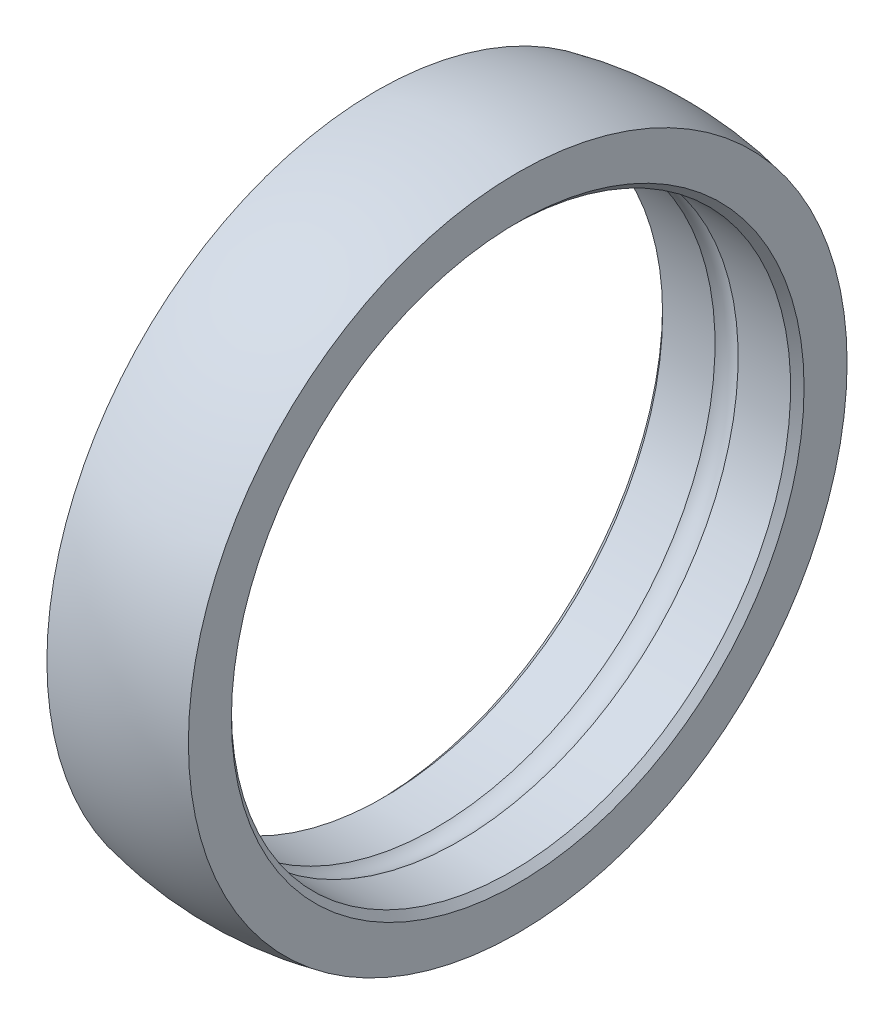
SolidWorks part; units mm, degrees
material "AISI 1045 钢，冷拔"
ref_plane "前视基准面" through (0, 0, 0) normal (0, 0, 1) x (1, 0, 0)
ref_plane "上视基准面" through (0, 0, 0) normal (0, 1, 0) x (1, 0, 0)
ref_plane "右视基准面" through (0, 0, 0) normal (1, 0, 0) x (0, 0, -1)
sketch "草图1" plane through (0, 0, 0) normal (0, 0, 1) x (1, 0, 0)
  line L0 (-55.2708, 0) -> (53.0251, 0) construction
  line L1 (0, 0) -> (0, 56.1931) construction
  line L7 (-10.5, 41.5) -> (-1.7176, 41.5)
  line L8 (1.7176, 41.5) -> (10.5, 41.5)
  line L10 (10.5, 48.8851) -> (10.5, 41.5)
  line L12 (-10.5, 48.8851) -> (-10.5, 41.5)
  arc A0 (10.5, 48.8851) -> (-10.5, 48.8851) centre (0, 0) ccw
  arc A1 (1.7176, 41.5) -> (-1.7176, 41.5) centre (0, 38.8) ccw
  dimension "D2" = 3.2
  dimension "D4" = 50
  dimension "D1" = 38.8
  dimension "D3" = 21
  dimension "D5" = 41.5
revolve "旋转1" add sketch "草图1" angle 360 about L0
chamfer "倒角1" distance 1 angle 45 2 edges at (-10.5, 0, 41.5) (10.5, 0, 41.5)
